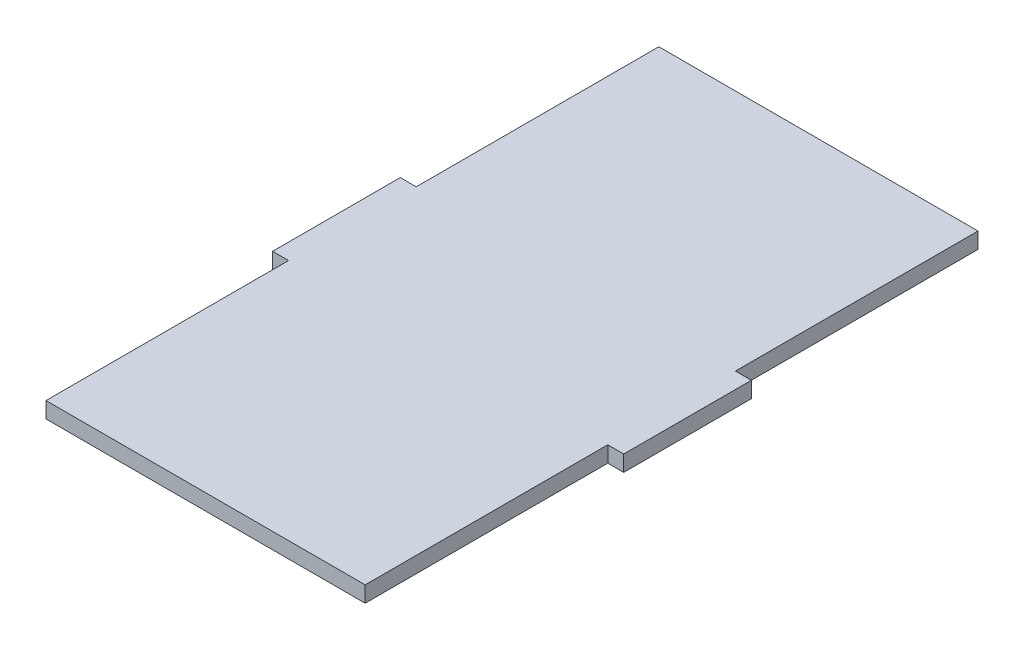
SolidWorks part; units mm, degrees
ref_plane "Front Plane" through (0, 0, 0) normal (0, 0, 1) x (1, 0, 0)
ref_plane "Top Plane" through (0, 0, 0) normal (0, 1, 0) x (1, 0, 0)
ref_plane "Right Plane" through (0, 0, 0) normal (1, 0, 0) x (0, 0, -1)
sketch "Sketch1" plane through (0, 0, 0) normal (0, 1, 0) x (1, 0, 0)
  line L1 (3.175, -29.21) -> (66.675, -29.21)
  line L2 (0, 19.05) -> (0, 44.45)
  line L3 (3.175, 92.71) -> (66.675, 92.71)
  line L4 (69.85, 19.05) -> (69.85, 44.45)
  line L7 (0, 19.05) -> (3.175, 19.05)
  line L8 (3.175, -29.21) -> (3.175, 19.05)
  line L10 (66.675, -29.21) -> (66.675, 19.05)
  line L11 (69.85, 19.05) -> (66.675, 19.05)
  line L12 (69.85, 44.45) -> (66.675, 44.45)
  line L13 (66.675, 92.71) -> (66.675, 44.45)
  line L14 (3.175, 92.71) -> (3.175, 44.45)
  line L15 (0, 44.45) -> (3.175, 44.45)
  dimension "D1" = 121.92
  dimension "D2" = 25.4
  dimension "D3" = 48.26
  dimension "D4" = 3.175
  dimension "D5" = 63.5
  dimension "D6" = 63.5
extrude "Boss-Extrude1" add sketch "Sketch1" along normal blind 3.175 contours L2 L15 L14 L3 L13 L12 L4 L11 L10 L1 L8 L7
